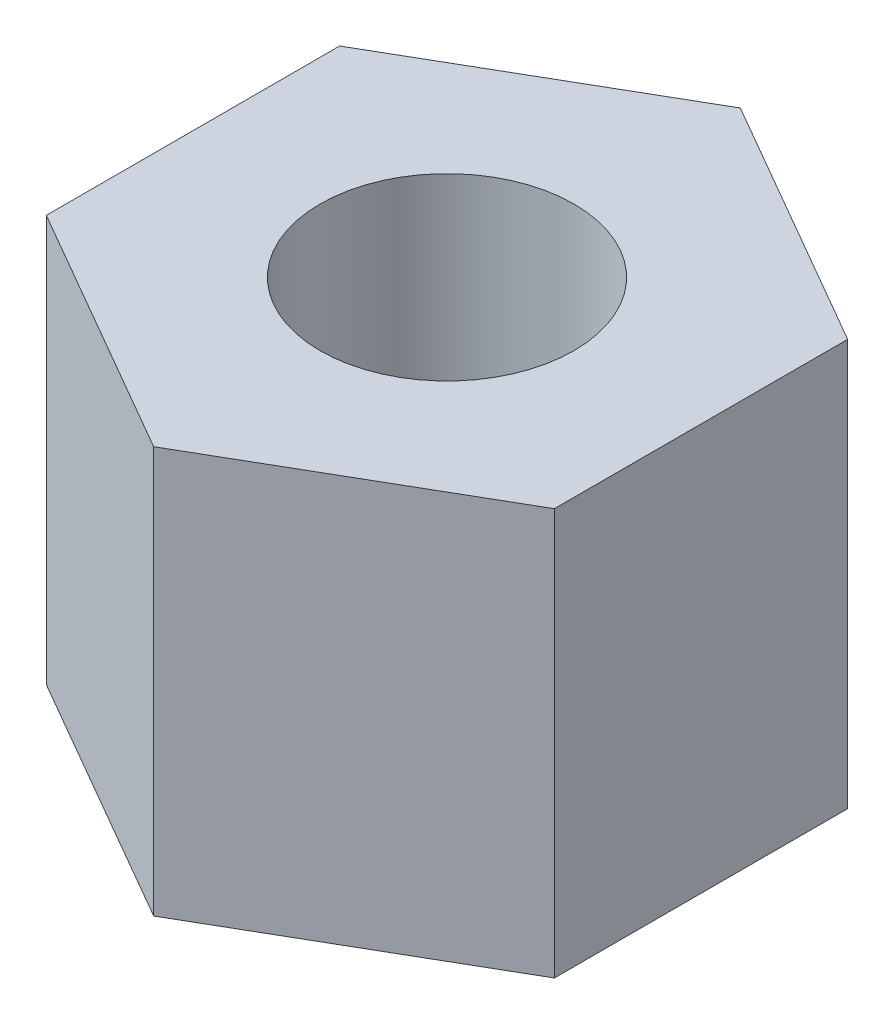
SolidWorks part; units mm, degrees
material "Tin Bearing Bronze"
ref_plane "Front Plane" through (0, 0, 0) normal (0, 0, 1) x (1, 0, 0)
ref_plane "Top Plane" through (0, 0, 0) normal (0, 1, 0) x (1, 0, 0)
ref_plane "Right Plane" through (0, 0, 0) normal (1, 0, 0) x (0, 0, -1)
sketch "Sketch2" plane through (0, 0, 0) normal (0, 1, 0) x (1, 0, 0)
  line L0 (0, 2.8868) -> (-2.5, 1.4434)
  line L1 (-2.5, 1.4434) -> (-2.5, -1.4434)
  line L2 (-2.5, -1.4434) -> (0, -2.8868)
  line L3 (0, -2.8868) -> (2.5, -1.4434)
  line L4 (2.5, -1.4434) -> (2.5, 1.4434)
  line L5 (2.5, 1.4434) -> (0, 2.8868)
  line L6 (0, -2.8868) -> (2.5, 1.4434)
  line L7 (2.5, -1.4434) -> (0, 2.8868)
  line L8 (-2.5, 1.4434) -> (2.5, 1.4434)
  line L9 (-2.5, -1.4434) -> (2.5, 1.4434) construction
  point P0 (0, 0)
  dimension "D1" = 5
extrude "Boss-Extrude1" add sketch "Sketch2" along normal blind 4 contours L9 L2 L6 L7 | L1 L9 L7 L8 | L0 L8 L7 | L7 L8 L5 | L7 L9 L8 | L9 L7 L6 | L7 L4 L6 | L3 L7 L6
hole_wizard "M3x0.5 Tapped Hole1" positions "Sketch8" profile "Sketch7" tap size "M3x0.5" standard "ANSI Metric"
sketch "Sketch8" plane through (0, 0, 0) normal (0, -1, 0) x (-1, 0, 0)
  point P0 (0, 0)
sketch "Sketch7" plane through (0, 0, 0) normal (1, 0, 0) x (0, 0, -1)
  line L0 (0, 0) -> (0, 14.2511)
  line L1 (0, 14.2511) -> (1.25, 13.5)
  line L2 (1.25, 13.5) -> (1.25, 0)
  line L5 (1.25, 0) -> (0, 0)
  line L10 (0, 14.2511) -> (-1.25, 13.5) construction
  line L11 (0, -6.35) -> (0, 107.95) construction
  dimension "Tap Drill Dia." = 2.5
  dimension "Tap Drill Depth" = 13.5
  dimension "Drill Angle" = 118
cosmetic thread "Hole Thread1" parameters "D1"=4, "D2"=3
